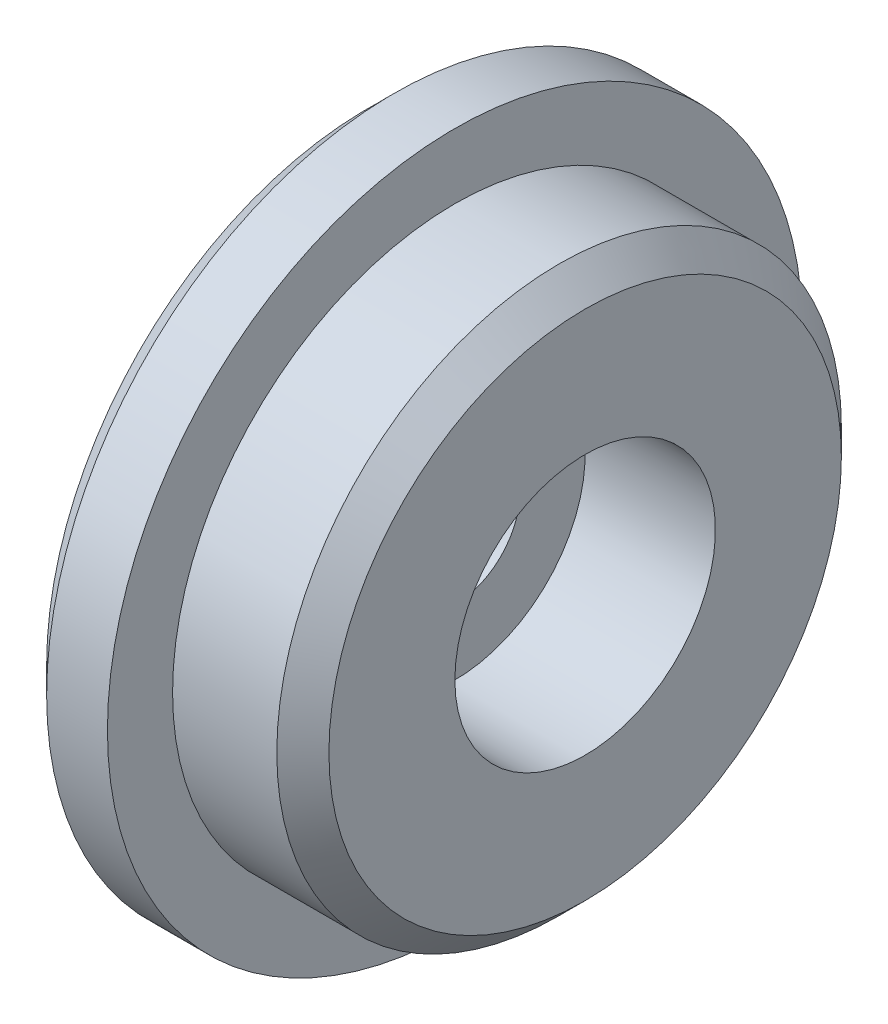
SolidWorks part; units mm, degrees
ref_plane "Front Plane" through (0, 0, 0) normal (0, 0, 1) x (1, 0, 0)
ref_plane "Top Plane" through (0, 0, 0) normal (0, 1, 0) x (1, 0, 0)
ref_plane "Right Plane" through (0, 0, 0) normal (1, 0, 0) x (0, 0, -1)
sketch "Sketch1" plane through (0, 0, 0) normal (0, 0, 1) x (1, 0, 0)
  line L0 (-0.6001, -4.7625) -> (-0.6001, -25.4)
  line L1 (-0.6001, -25.4) -> (5.7499, -25.4)
  line L2 (5.7499, -25.4) -> (5.7499, -20.6375)
  line L3 (5.7499, -20.6375) -> (15.2749, -20.6375)
  line L4 (15.2749, -20.6375) -> (15.2749, -9.525)
  line L5 (15.2749, -9.525) -> (5.7499, -9.525)
  line L6 (5.7499, -9.525) -> (5.7499, -4.7625)
  line L7 (5.7499, -4.7625) -> (-0.6001, -4.7625)
  line L8 (0, 0) -> (39.2784, 0) construction
  dimension "D1" = 50.8
  dimension "D2" = 9.525
  dimension "D3" = 19.05
  dimension "D4" = 41.275
  dimension "D5" = 6.35
  dimension "D6" = 9.525
revolve "Revolve1" add sketch "Sketch1" angle 360 about L8
chamfer "Chamfer1" distance 1.905 angle 45 2 edges at (-0.6001, 0, 25.4) (15.2749, 0, 20.6375)
